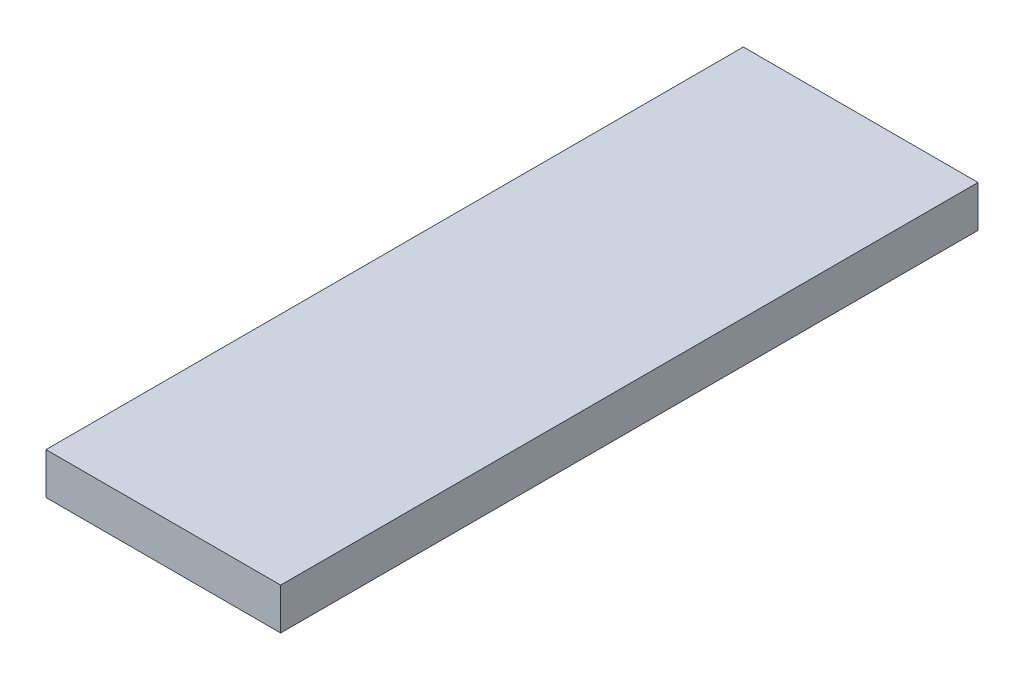
SolidWorks part; units mm, degrees
ref_plane "Front Plane" through (0, 0, 0) normal (0, 0, 1) x (1, 0, 0)
ref_plane "Top Plane" through (0, 0, 0) normal (0, 1, 0) x (1, 0, 0)
ref_plane "Right Plane" through (0, 0, 0) normal (1, 0, 0) x (0, 0, -1)
sketch "Sketch1" plane through (0, 0, 0) normal (0, 1, 0) x (1, 0, 0)
  line L1 (0, 0) -> (53.848, 0)
  line L2 (0, 0) -> (0, 160.02)
  line L3 (0, 160.02) -> (53.848, 160.02)
  line L4 (53.848, 0) -> (53.848, 160.02)
  dimension "D1" = 160.02
  dimension "D2" = 53.848
extrude "Boss-Extrude1" add sketch "Sketch1" along normal blind 9.525
